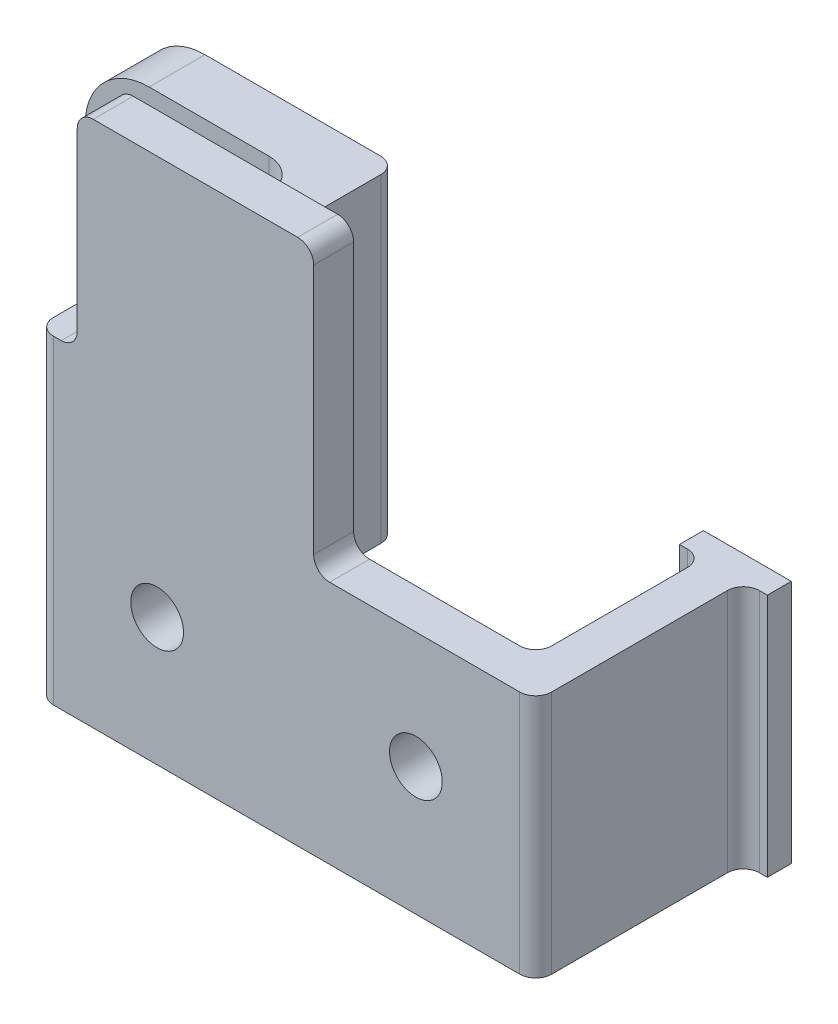
SolidWorks part; units mm, degrees
ref_plane "Front Plane" through (0, 0, 0) normal (0, 0, 1) x (1, 0, 0)
ref_plane "Top Plane" through (0, 0, 0) normal (0, 1, 0) x (1, 0, 0)
ref_plane "Right Plane" through (0, 0, 0) normal (1, 0, 0) x (0, 0, -1)
sketch "Sketch1" plane through (0, 0, 0) normal (0, 0, 1) x (1, 0, 0)
  line L0 (-13.1, -1.2) -> (13.1, -1.2)
  line L1 (13.1, 16.5) -> (1.7, 16.5) construction
  line L2 (13.1, 16.5) -> (13.1, -16.5)
  line L3 (13.1, -16.5) -> (-13.1, -16.5)
  line L4 (-13.1, -1.2) -> (-13.1, -16.5)
  line L5 (13.1, 16.5) -> (-13.1, -16.5) construction
  line L6 (13.1, -16.5) -> (1.7, -2.1412) construction
  line L7 (1.7, -1.2) -> (1.7, 16.5)
  line L8 (-8.1, -8.5) -> (8.1, -8.5) construction
  line L9 (1.7, 16.5) -> (-13.1, 16.5)
  line L10 (-13.1, 16.5) -> (-13.1, -1.2)
  circle A0 centre (8.1, -8.5) radius 1.65
  circle A1 centre (-8.1, -8.5) radius 1.65
  point P0 (0, 0)
  dimension "D5" = 3.3
  dimension "D6" = 3.3
  dimension "D1" = 33
  dimension "D2" = 26.2
  dimension "D3" = 15.3
  dimension "D4" = 14.8
  dimension "D7" = 8
  dimension "D8" = 5
  dimension "D9" = 5
  dimension "D10" = 2.0809
extrude "Boss-Extrude1" add sketch "Sketch1" along normal blind 2.5 contours L9 L10 L0 L7 | L0 L4 L3 L2 A1 A0
fillet "Fillet1" radius 1 2 edges at (-13.1, 16.5, 1.25) (1.7, 16.5, 1.25)
sketch "Sketch6" plane through (-13.1, 0, 0) normal (-1, 0, 0) x (0, 0, 1)
  line L0 (2.5, -16.5) -> (2.5, 3.5)
  line L1 (2.5, 15.5) -> (2.5, -16.5) construction
  line L2 (2.5, 3.5) -> (-14, 3.5)
  line L3 (-14, 3.5) -> (-14, -16.5)
  line L4 (-14, -16.5) -> (2.5, -16.5)
  line L5 (0, 15.5) -> (0, -16.5) construction
  dimension "D1" = 16.5
  dimension "D2" = 14
  dimension "D3" = 20
extrude "Boss-Extrude8" add sketch "Sketch6" along normal blind 2.5
sketch "Sketch7" plane through (0, 0, -14) normal (0, 0, -1) x (-1, 0, 0)
  line L0 (13.1, 3.5) -> (29.1, 3.5)
  line L1 (29.1, 3.5) -> (29.1, -16.5)
  line L2 (29.1, -16.5) -> (13.1, -16.5)
  line L3 (13.1, -16.5) -> (13.1, 3.5)
  line L4 (25.6, -5.1) -> (25.6, -10.5)
  line L5 (20.2, -5.1) -> (20.2, -10.5)
  circle A0 centre (22.9, -5.1) radius 2.7
  circle A1 centre (22.9, -10.5) radius 2.7
  line M7 (13.1, 3.5) -> (13.1, -16.5)
  line M8 (13.1, -16.5) -> (15.6, -16.5)
  line M9 (15.6, -16.5) -> (15.6, 3.5)
  line M10 (15.6, 3.5) -> (13.1, 3.5)
  dimension "D2" = 5.4
  dimension "D3" = 6
  dimension "D1" = 16
  dimension "D4" = 6.2
extrude "Boss-Extrude9" add sketch "Sketch7" along normal blind 3.5 contours L2 L1 L0 A1 L5 A0 L4 M9 | M10 M7 M8 M9
fillet "Fillet5" radius 2 2 edges at (-15.6, -6.5, -14) (-13.1, -6.5, 0)
fillet "Fillet6" radius 1 2 edges at (-13.1, 3.5, 1.25) (-15.6, -6.5, 2.5)
sketch "Sketch10" plane through (13.1, 0, 0) normal (1, 0, 0) x (0, 0, -1)
  line L0 (-2.5, -1.2) -> (12, -1.2)
  line L1 (12, -1.2) -> (12, -16.5)
  line L2 (12, -16.5) -> (-2.5, -16.5)
  line L3 (-2.5, -16.5) -> (-2.5, -1.2)
  line L4 (0, -1.2) -> (0, -16.5) construction
  dimension "D1" = 12
extrude "Boss-Extrude10" add sketch "Sketch10" along normal blind 2.5
sketch "Sketch11" plane through (0, 0, -12) normal (0, 0, -1) x (-1, 0, 0)
  line L0 (-14.35, -1.2) -> (-14.35, -16.5) construction
  line L1 (-15.6, -1.2) -> (-13.1, -1.2) construction
  line L2 (-15.6, -16.5) -> (-13.1, -16.5) construction
  line L3 (-13.1, -16.5) -> (-13.1, -1.2) construction
  line L4 (-11.6, -1.2) -> (-17.1, -1.2)
  line L5 (-11.6, -1.2) -> (-11.6, -16.5)
  line L6 (-11.6, -16.5) -> (-17.1, -16.5)
  line L7 (-17.1, -1.2) -> (-17.1, -16.5)
  line L8 (-11.6, -1.2) -> (-17.1, -16.5) construction
  line L9 (-11.6, -16.5) -> (-17.1, -1.2) construction
  point P6 (-14.35, -8.85)
  dimension "D1" = 1.5
extrude "Boss-Extrude11" add sketch "Sketch11" against normal blind 1.5
fillet "Fillet7" radius 1 6 edges at (1.7, -1.2, 1.25) (13.1, -8.85, 0) (15.6, -8.85, 2.5) (13.1, -8.85, -10.5) (15.6, -8.85, -10.5) (-13.1, -6.5, -17.5)
fillet "Fillet8" radius 4 2 edges at (-29.1, 3.5, -15.75) (-29.1, -16.5, -15.75)
